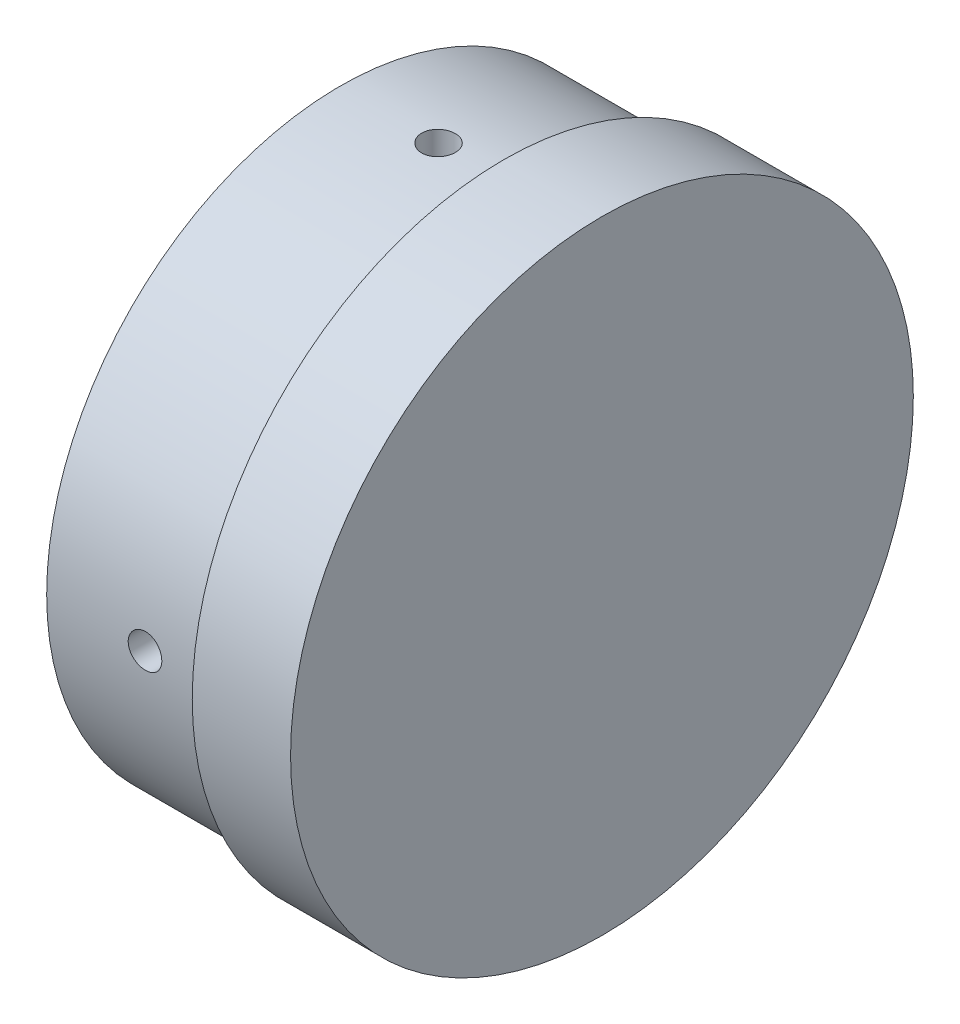
SolidWorks part; units mm, degrees
material "6061-T6 (SS)"
ref_plane "Front Plane" through (0, 0, 0) normal (0, 0, 1) x (1, 0, 0)
ref_plane "Top Plane" through (0, 0, 0) normal (0, 1, 0) x (1, 0, 0)
ref_plane "Right Plane" through (0, 0, 0) normal (1, 0, 0) x (0, 0, -1)
sketch "Sketch1" plane through (0, 0, 0) normal (0, 0, 1) x (1, 0, 0)
  line L0 (-76.2427, 0) -> (91.437, 0) construction
  line L1 (0, 17.8825) -> (0, 17.9125)
  line L2 (0, 17.9125) -> (9.97, 17.9125)
  line L3 (9.97, 17.9125) -> (9.97, 19)
  line L4 (9.97, 19) -> (15.97, 19)
  line L5 (15.97, 19) -> (15.97, 17)
  line L9 (0, 17.8825) -> (0, 0)
  line L10 (15.97, 17) -> (15.97, 0)
  dimension "D1" = 0.03
  dimension "D3" = 6
  dimension "D5" = 2
  dimension "D6" = 17
revolve "Revolve1" add sketch "Sketch1" angle 360 about L0
hole_wizard "M2.5 Tapped Hole1" positions "3DSketch2" profile "Sketch4" tap size "M2.5" standard "ISO"
sketch3d "3DSketch2"
  point P0 (6, -17.9125, 0)
  point P2 (6, 0, 17.9125)
  point P4 (-38.2986, 0, -8.0349)
  dimension "D1" = 6
  dimension "D2" = 6
  dimension "D3" = 6
cosmetic thread "Hole Thread1" parameters "D1"=3.55, "D2"=2.5
cosmetic thread "Hole Thread2" parameters "D1"=3.55, "D2"=2.5
sketch "Sketch4" plane through (6, -17.9125, 0) normal (1, 0, 0) x (0, 0, -1)
  line L0 (0, 0) -> (0, 4.6159)
  line L1 (0, 4.6159) -> (1.025, 4)
  line L2 (1.025, 4) -> (1.025, 0)
  line L5 (1.025, 0) -> (0, 0)
  line L10 (0, 4.6159) -> (-1.025, 4) construction
  line L11 (0, -6.35) -> (0, 107.95) construction
  dimension "Tap Drill Dia." = 2.05
  dimension "Tap Drill Depth" = 4
  dimension "Drill Angle" = 118
hole_wizard "M2.5 Tapped Hole2" positions "3DSketch3" profile "Sketch5" tap size "M2.5" standard "ISO"
sketch3d "3DSketch3"
  point P0 (6, 0, -17.9125)
  point P2 (6, 17.9125, 0)
  dimension "D1" = 6
  dimension "D2" = 6
  dimension "D3" = 6
sketch "Sketch5" plane through (6, 0, -17.9125) normal (1, 0, 0) x (0, 1, 0)
  line L0 (0, 0) -> (0, 5.5159)
  line L1 (0, 5.5159) -> (1.025, 4.9)
  line L2 (1.025, 4.9) -> (1.025, 0)
  line L5 (1.025, 0) -> (0, 0)
  line L10 (0, 5.5159) -> (-1.025, 4.9) construction
  line L11 (0, -6.35) -> (0, 107.95) construction
  dimension "Tap Drill Dia." = 2.05
  dimension "Tap Drill Depth" = 4.9
  dimension "Drill Angle" = 118
cosmetic thread "Hole Thread3" parameters "D1"=3.55, "D2"=2.5
cosmetic thread "Hole Thread4" parameters "D1"=3.55, "D2"=2.5
